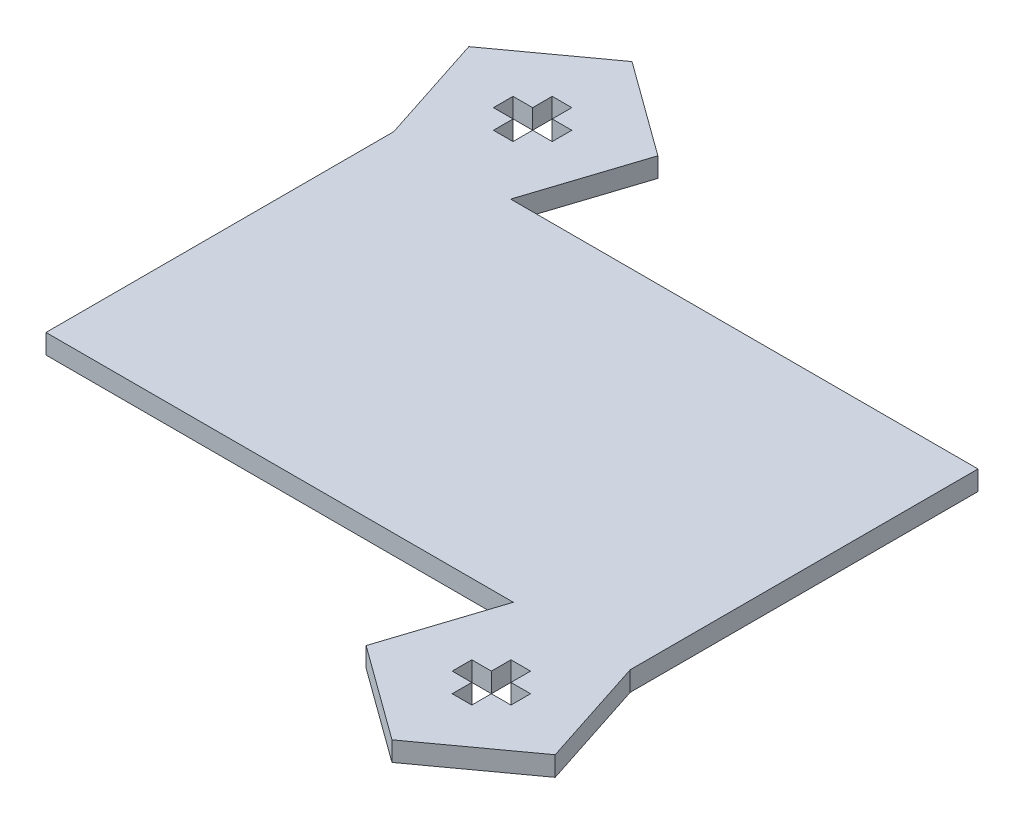
SolidWorks part; units mm, degrees
ref_plane "Front Plane" through (0, 0, 0) normal (0, 0, 1) x (1, 0, 0)
ref_plane "Top Plane" through (0, 0, 0) normal (0, 1, 0) x (1, 0, 0)
ref_plane "Right Plane" through (0, 0, 0) normal (1, 0, 0) x (0, 0, -1)
sketch "Sketch1" plane through (0, 0, 0) normal (0, 1, 0) x (1, 0, 0)
  line L0 (-44.4916, 36.825) -> (-44.4916, -53.3348) construction
  line L1 (-14.2021, -53.3348) -> (-14.2021, 36.825) construction
  line L2 (-74.7837, 36.825) -> (-74.783, 36.825)
  line L3 (-74.7837, 36.825) -> (-74.7837, -53.3348)
  line L4 (-74.7837, -53.3348) -> (46.375, -53.3348)
  line L5 (76.6664, 36.825) -> (76.6664, -53.3348)
  line L6 (16.0874, -53.3348) -> (16.0874, 36.825) construction
  line L7 (46.3769, -53.3348) -> (46.3769, 36.825) construction
  line L8 (-106.6412, 57.6708) -> (145.2107, 57.6708) construction
  line L9 (-106.6412, -74.1806) -> (170.8946, -74.1806) construction
  line L10 (-59.6377, -97.0592) -> (-59.6377, 74.4993) construction
  line L11 (61.5203, 72.7538) -> (61.5203, -97.0592) construction
  line L12 (-59.6377, 65.2908) -> (-57.0977, 65.2908)
  line L13 (-44.4916, 36.825) -> (-35.1318, 65.6338)
  line L14 (-35.1318, 65.6338) -> (-59.6382, 83.438)
  line L15 (-59.6382, 83.438) -> (-84.1439, 65.6328)
  line L16 (-84.1439, 65.6328) -> (-74.783, 36.825)
  line L17 (-59.6377, 36.8247) -> (-59.6372, 36.8247)
  line L19 (46.375, -53.3348) -> (37.0141, -82.1426)
  line L20 (37.0141, -82.1426) -> (61.5198, -99.9478)
  line L21 (61.5198, -99.9478) -> (86.0262, -82.1436)
  line L22 (86.0262, -82.1436) -> (76.6664, -53.3348)
  line L23 (-57.0977, 65.2908) -> (-57.0977, 60.2108)
  line L24 (-57.0977, 60.2108) -> (-52.0177, 60.2108)
  line L25 (-52.0177, 60.2108) -> (-52.0177, 57.6708)
  line L26 (-52.0177, 57.6708) -> (-52.0177, 55.1308)
  line L27 (-52.0177, 55.1308) -> (-57.0977, 55.1308)
  line L28 (-57.0977, 55.1308) -> (-57.0977, 50.0508)
  line L29 (-57.0977, 50.0508) -> (-59.6377, 50.0508)
  line L30 (-59.6377, 50.0508) -> (-62.1777, 50.0508)
  line L31 (-62.1777, 50.0508) -> (-62.1777, 55.1308)
  line L32 (-62.1777, 55.1308) -> (-67.2577, 55.1308)
  line L33 (-67.2577, 55.1308) -> (-67.2577, 57.6708)
  line L34 (-67.2577, 57.6708) -> (-67.2577, 60.2108)
  line L35 (-67.2577, 60.2108) -> (-62.1777, 60.2108)
  line L36 (-62.1777, 60.2108) -> (-62.1777, 65.2908)
  line L37 (-62.1777, 65.2908) -> (-59.6377, 65.2908)
  line L38 (69.1403, -74.1806) -> (69.1403, -76.7206)
  line L39 (69.1403, -71.6406) -> (69.1403, -74.1806)
  line L40 (58.9803, -66.5606) -> (61.5203, -66.5606)
  line L41 (64.0603, -81.8006) -> (61.5203, -81.8006)
  line L42 (53.9003, -76.7206) -> (53.9003, -74.1806)
  line L43 (69.1403, -76.7206) -> (64.0603, -76.7206)
  line L44 (61.5203, -81.8006) -> (58.9803, -81.8006)
  line L45 (64.0603, -71.6406) -> (69.1403, -71.6406)
  line L46 (64.0603, -66.5606) -> (64.0603, -71.6406)
  line L47 (53.9003, -71.6406) -> (58.9803, -71.6406)
  line L48 (58.9803, -76.7206) -> (53.9003, -76.7206)
  line L49 (58.9803, -81.8006) -> (58.9803, -76.7206)
  line L50 (53.9003, -74.1806) -> (53.9003, -71.6406)
  line L51 (61.5203, -66.5606) -> (64.0603, -66.5606)
  line L52 (64.0603, -76.7206) -> (64.0603, -81.8006)
  line L53 (58.9803, -71.6406) -> (58.9803, -66.5606)
  line L54 (-44.4916, 36.825) -> (76.6664, 36.825)
  line L57 (61.5208, -53.3345) -> (61.5203, -53.3345) [skipped]
  circle A0 centre (-59.6377, 57.6708) radius 20.8461 construction
  circle A1 centre (61.5203, -74.1806) radius 20.8461 construction
  point P20 (-59.6377, 57.6708)
  point P21 (61.5203, -74.1806)
  point P37 (61.5203, -74.1806)
  point P57 (-59.6377, 57.6708)
  point P68 (61.5203, -74.1806)
  dimension "D11" = 2.54
  dimension "D1" = 151.45
  dimension "D2" = 90.1598
  dimension "D3" = 30.2895
  dimension "D4" = 30.2895
  dimension "D5" = 30.2895
  dimension "D6" = 30.2895
  dimension "D7" = 20.8458
  dimension "D8" = 20.8458
  dimension "D9" = 15.146
  dimension "D10" = 15.146
  dimension "D12" = 2.54
  dimension "D13" = 5.08
  dimension "D14" = 5.08
  dimension "D15" = 5.08
  dimension "D16" = 5.08
extrude "Boss-Extrude1" add sketch "Sketch1" along normal blind 5.08
sketch "Sketch2" plane through (0, 5.08, 0) normal (0, 1, 0) x (1, 0, 0)
  line L0 (-74.7837, -53.3348) -> (76.6664, 36.825) construction
  line L1 (76.6664, -53.3348) -> (-74.7837, 36.825) construction
  line L2 (-74.7837, -8.2549) -> (76.6664, -8.2549) construction
  line L3 (-74.7837, 36.825) -> (-74.7837, -53.3348) construction
  line L4 (76.6664, 36.825) -> (76.6664, -53.3348) construction
  line L5 (-74.7837, 31.745) -> (76.6664, 31.745) construction
  line L6 (76.6664, -48.2548) -> (-74.7837, -48.2548) construction
  line L7 (-44.4916, 36.825) -> (76.6664, 36.825) construction
  line L8 (-74.7837, -53.3348) -> (46.375, -53.3348) construction
  line L9 (-74.7837, -23.4009) -> (76.6664, -23.4009) construction
  line L10 (-74.7837, 6.8911) -> (76.6664, 6.8911) construction
  line L11 (-44.4916, 36.825) -> (-44.4916, -53.3348) construction
  line L12 (-14.2021, 36.825) -> (-14.2021, -53.3348) construction
  line L13 (16.0874, 36.825) -> (16.0874, -53.3348) construction
  line L14 (46.375, -53.3348) -> (46.375, 36.825) construction
  point P6 (0.9413, -8.2549)
  dimension "D1" = 5.08
  dimension "D2" = 5.08
  dimension "D3" = 15.146
  dimension "D5" = 30.2895
  dimension "D6" = 30.2895
  dimension "D4" = 15.146
